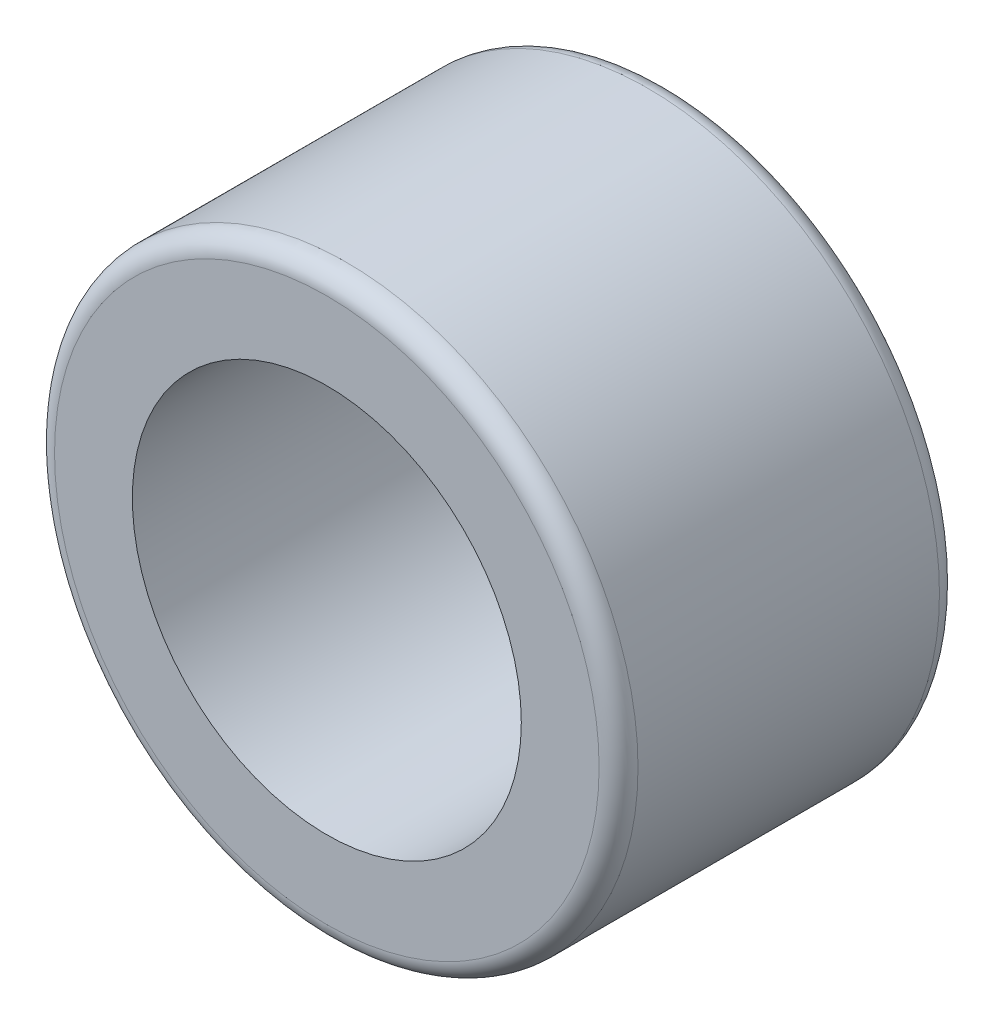
SolidWorks part; units mm, degrees
ref_plane "前视基准面" through (0, 0, 0) normal (0, 0, 1) x (1, 0, 0)
ref_plane "上视基准面" through (0, 0, 0) normal (0, 1, 0) x (1, 0, 0)
ref_plane "右视基准面" through (0, 0, 0) normal (1, 0, 0) x (0, 0, -1)
sketch "草图1" plane through (0, 0, 0) normal (0, 0, 1) x (1, 0, 0)
  circle A0 centre (0, 0) radius 2
  circle A1 centre (0, 0) radius 3
extrude "凸台-拉伸1" add sketch "草图1" against normal blind 3.5
fillet "圆角1" radius 0.2 2 edges at (3, 0, -3.5) (3, 0, 0)
